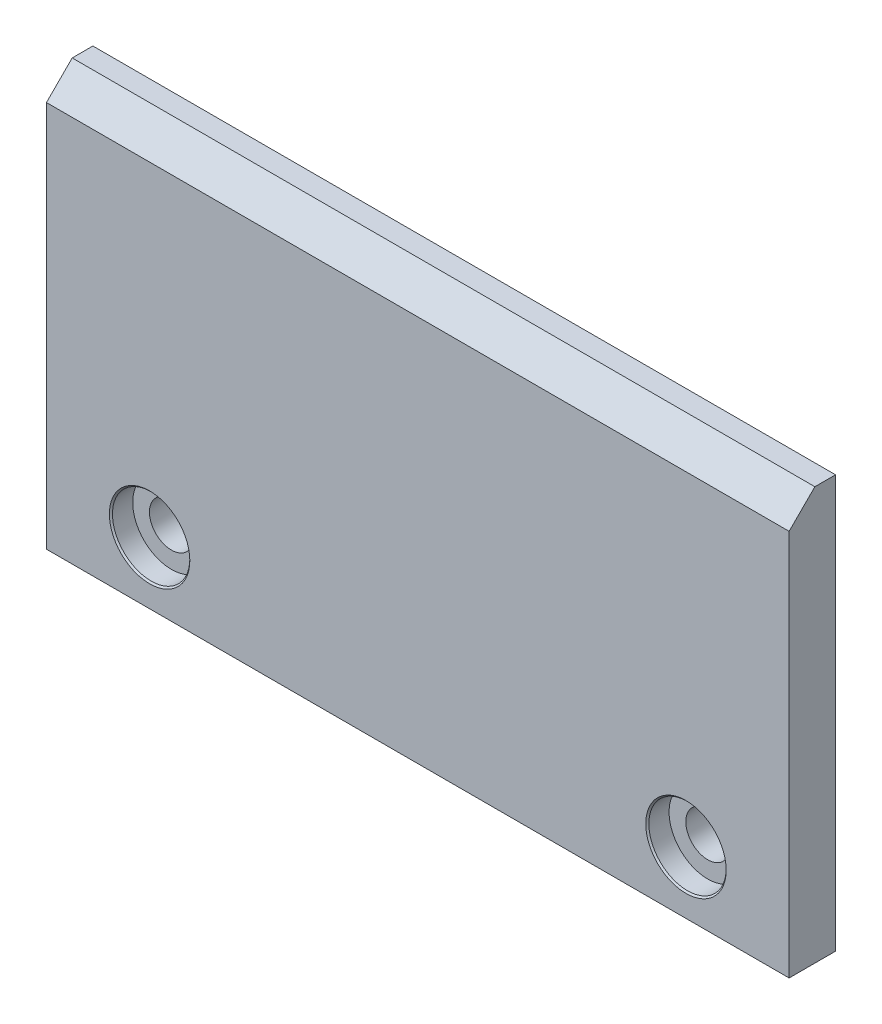
SolidWorks part; units mm, degrees
material "AISI 1020 Steel, Cold Rolled"
ref_plane "Front" through (0, 0, 0) normal (0, 0, 1) x (1, 0, 0)
ref_plane "Top" through (0, 0, 0) normal (0, 1, 0) x (1, 0, 0)
ref_plane "Right" through (0, 0, 0) normal (1, 0, 0) x (0, 0, -1)
sketch "Sketch2" plane through (0, 0, 0) normal (1, 0, 0) x (0, 0, -1)
  line L0 (0, 0) -> (0, 63.5)
  line L2 (0, 63.5) -> (7.1438, 63.5)
  line L3 (7.1438, 63.5) -> (7.1438, 0)
  line L4 (7.1438, 0) -> (0, 0)
  dimension "D1" = 63.5
  dimension "D2" = 7.1437
extrude "Boss-Extrude1" add sketch "Sketch2" against normal blind 114.3
hole_wizard "CBORE for 1/4 Button Head Cap Screw1" positions "Sketch4" profile "Sketch3" counterbore size "1/4" standard "ANSI Inch" end condition through all
sketch "Sketch4" plane through (0, 0, 0) normal (0, 0, 1) x (1, 0, 0)
  line L0 (-114.3, 63.5) -> (-114.3, 0) construction
  line L1 (0, 63.5) -> (0, 0) construction
  line L2 (-114.3, 0) -> (0, 0) construction
  point P0 (-98.425, 9.525)
  point P2 (-15.875, 9.525)
  dimension "D1" = 15.875
  dimension "D2" = 15.875
  dimension "D3" = 9.525
sketch "Sketch3" plane through (-98.425, 9.525, 0) normal (1, 0, 0) x (0, -1, 0)
  line L0 (0, 0) -> (0, 7.1438)
  line L1 (0, 7.1438) -> (3.3782, 7.1438)
  line L3 (3.3782, 7.1438) -> (3.3782, 3.3528)
  line L4 (5.9538, 3.3528) -> (3.3782, 3.3528)
  line L5 (5.9538, 3.3528) -> (5.9538, 0.2375)
  line L6 (5.9538, 0.2375) -> (6.1912, 0)
  line L7 (6.1912, 0) -> (0, 0)
  line L8 (-5.9538, 0.2375) -> (-6.1912, 0) construction
  line L11 (0, -6.35) -> (0, 107.95) construction
  dimension "Thru Hole Dia." = 6.7564
  dimension "Thru Hole Depth" = 7.1438
  dimension "C'Bore Dia." = 11.9075
  dimension "C'Bore Depth" = 3.3528
  dimension "Near C'Sink Dia." = 12.3825
  dimension "Near C'Sink Angle" = 90
chamfer "Chamfer1" distance 3.9624 angle 45 1 edges at (-57.15, 63.5, 0)
